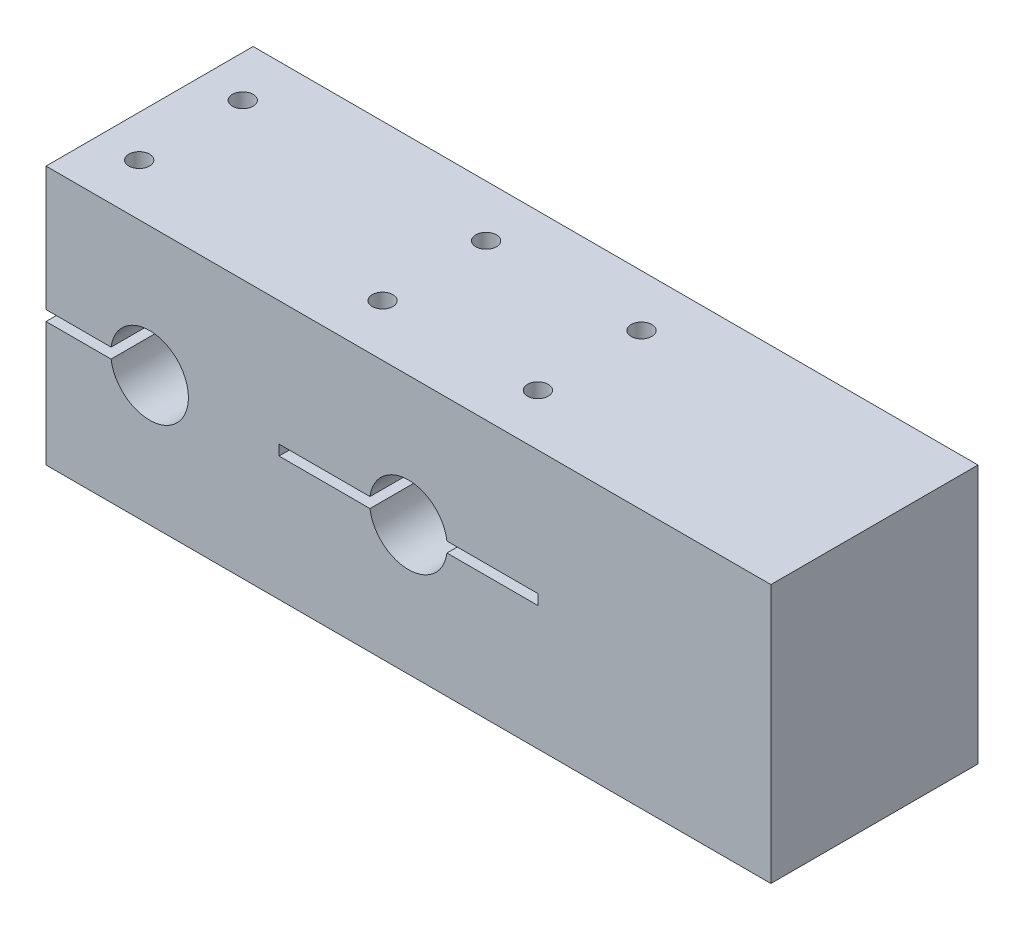
SolidWorks part; units mm, degrees
material "Сосна"
ref_plane "Спереди" through (0, 0, 0) normal (0, 0, 1) x (1, 0, 0)
ref_plane "Сверху" through (0, 0, 0) normal (0, 1, 0) x (1, 0, 0)
ref_plane "Справа" through (0, 0, 0) normal (1, 0, 0) x (0, 0, -1)
sketch "Эскиз1" plane through (0, 0, 0) normal (0, 0, 1) x (1, 0, 0)
  line L0 (62.567, 26) -> (45, 26)
  line L1 (0, 0) -> (140, 0)
  line L2 (0, 0) -> (0, 24)
  line L3 (0, 50) -> (140, 50)
  line L4 (140, 0) -> (140, 34)
  line L5 (77.433, 24) -> (94.9977, 24)
  line L6 (0, 26) -> (12.567, 26)
  line L7 (45, 26) -> (45, 24)
  line L8 (0, 24) -> (12.567, 24)
  line L9 (0, 26) -> (0, 50)
  line L10 (45, 24) -> (62.567, 24)
  line L11 (94.9977, 24) -> (94.9977, 26)
  line L12 (140, 34) -> (140, 50)
  line L13 (94.9977, 26) -> (77.433, 26)
  arc A0 (12.567, 24) -> (12.567, 26) centre (20, 25) ccw
  arc A1 (62.567, 24) -> (77.433, 24) centre (70, 25) ccw
  arc A2 (77.433, 26) -> (62.567, 26) centre (70, 25) ccw
  dimension "D5" = 50
  dimension "D4" = 25
  dimension "D1" = 140
  dimension "D2" = 50
  dimension "D3" = 20
  dimension "D6" = 2
  dimension "D7" = 1
  dimension "D8" = 25
extrude "Бобышка-Вытянуть1" add sketch "Эскиз1" along normal blind 40
sketch "Эскиз8" plane through (0, 0, 0) normal (0, -1, 0) x (1, 0, 0)
  line L0 (0, 40) -> (0, 0) construction
  line L1 (0, 40) -> (140, 40) construction
  line L2 (0, 0) -> (140, 0) construction
  circle A0 centre (8, 30) radius 2
  circle A1 centre (8, 10) radius 2
  circle A2 centre (55, 30) radius 2
  circle A3 centre (55, 10) radius 2
  circle A4 centre (85, 30) radius 2
  circle A5 centre (85, 10) radius 2
  dimension "D1" = 8
  dimension "D3" = 10
  dimension "D5" = 55
  dimension "D6" = 55
  dimension "D7" = 30
  dimension "D2" = 10
  dimension "D4" = 8
  dimension "D8" = 30
extrude "Вырез-Вытянуть5" cut sketch "Эскиз8" against normal blind 50
